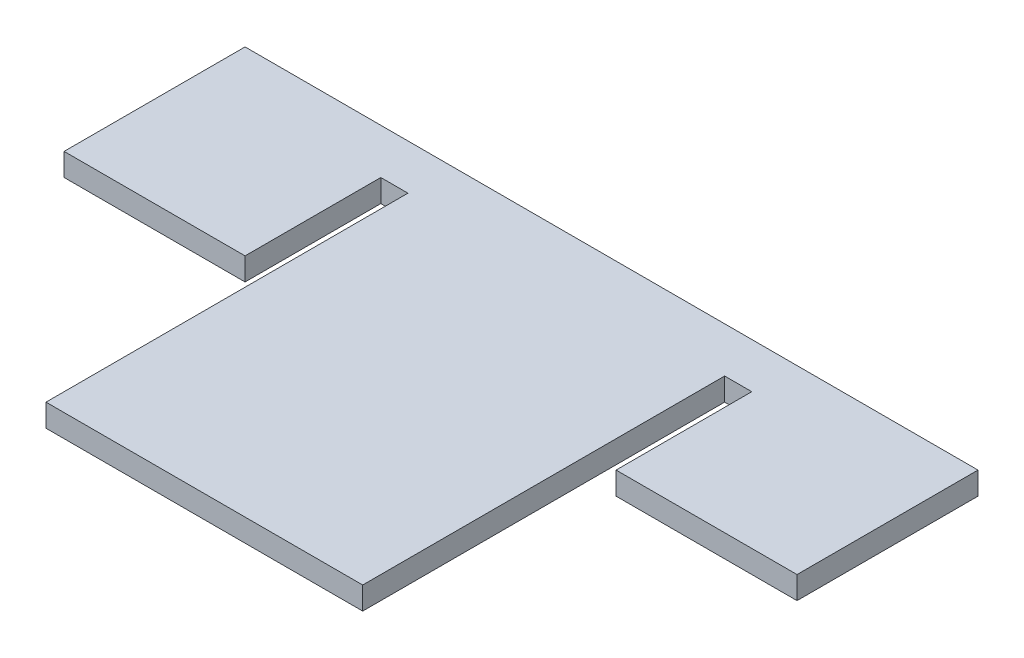
SolidWorks part; units mm, degrees
ref_plane "Front Plane" through (0, 0, 0) normal (0, 0, 1) x (1, 0, 0)
ref_plane "Top Plane" through (0, 0, 0) normal (0, 1, 0) x (1, 0, 0)
ref_plane "Right Plane" through (0, 0, 0) normal (1, 0, 0) x (0, 0, -1)
sketch "Sketch1" plane through (0, 0, 0) normal (0, 1, 0) x (1, 0, 0)
  line L0 (-29.21, 57.15) -> (73.66, 57.15)
  line L1 (73.66, 57.15) -> (73.66, 31.75)
  line L2 (0, 50.8) -> (0, 0)
  line L3 (0, 0) -> (44.45, 0)
  line L4 (44.45, 50.8) -> (44.45, 0)
  line L5 (-29.21, 57.15) -> (-29.21, 31.75)
  line L7 (0, 50.8) -> (-3.81, 50.8)
  line L11 (-29.21, 31.75) -> (-3.81, 31.75)
  line L12 (-3.81, 50.8) -> (-3.81, 31.75)
  line L15 (44.45, 50.8) -> (48.26, 50.8)
  line L19 (73.66, 31.75) -> (48.26, 31.75)
  line L20 (48.26, 50.8) -> (48.26, 31.75)
  dimension "D1" = 44.45
  dimension "D2" = 25.4
  dimension "D3" = 3.81
  dimension "D4" = 19.05
  dimension "D5" = 25.4
  dimension "D6" = 50.8
extrude "Boss-Extrude1" add sketch "Sketch1" along normal blind 3.175
